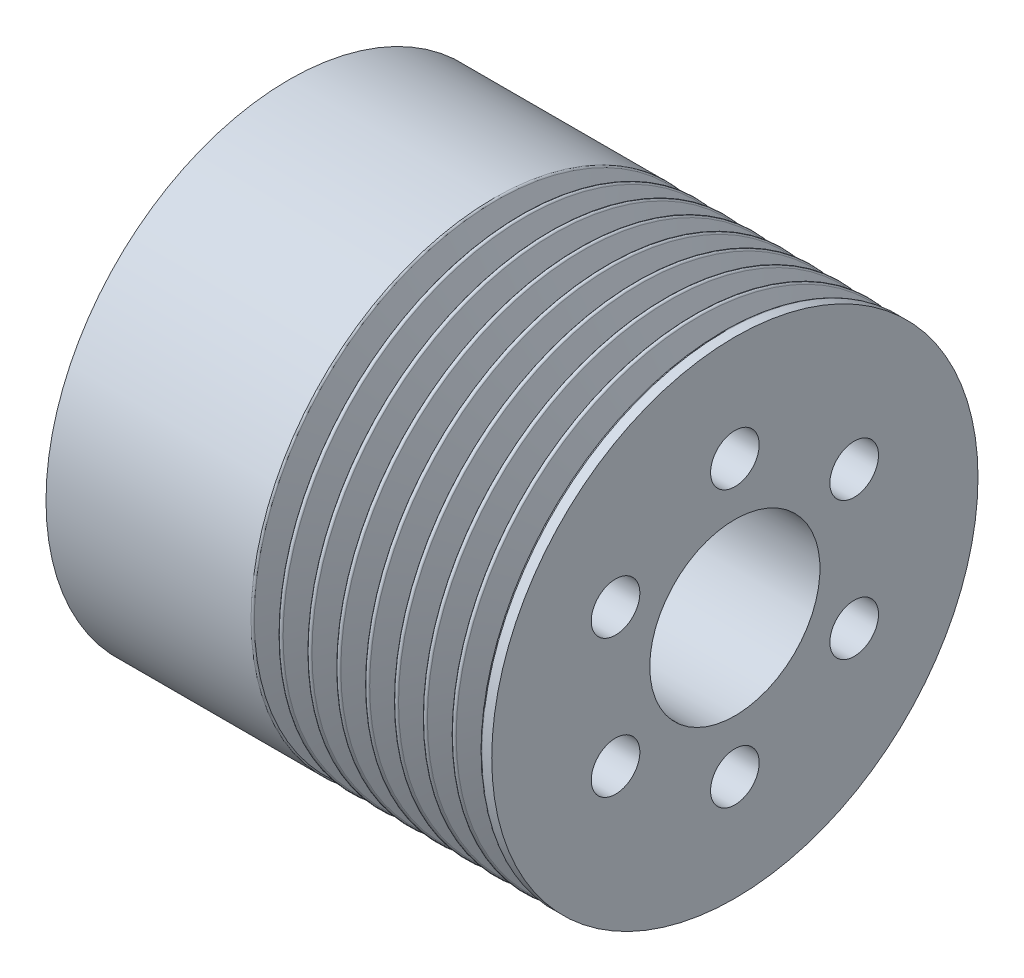
SolidWorks part; units mm, degrees
material "2018 Alloy"
ref_plane "Front Plane" through (0, 0, 0) normal (0, 0, 1) x (1, 0, 0)
ref_plane "Top Plane" through (0, 0, 0) normal (0, 1, 0) x (1, 0, 0)
ref_plane "Right Plane" through (0, 0, 0) normal (1, 0, 0) x (0, 0, -1)
sketch "Sketch1" plane through (0, 0, 0) normal (0, 0, 1) x (1, 0, 0)
  line L0 (49, 10.5) -> (49, 0) construction
  line L1 (49, 10.5) -> (49, 30)
  line L2 (49, 30) -> (-6, 30)
  line L3 (-6, 30) -> (-6, 21.5)
  line L4 (49, 10.5) -> (31.5, 10.5)
  line L5 (0, 0) -> (49, 0) construction
  line L6 (-6, 21.5) -> (31.5, 21.5)
  line L8 (0, 8.3175) -> (0, 0) construction
  line L9 (31.5, 10.5) -> (31.5, 21.5)
  dimension "D1" = 55
  dimension "D2" = 60
  dimension "D3" = 31.5
  dimension "D4" = 43
  dimension "D5" = 49
  dimension "D8" = 21
revolve "Revolve1" add sketch "Sketch1" angle 360 about L5
sketch "Sketch2" plane through (0, 0, 0) normal (0, 0, 1) x (1, 0, 0)
  line L0 (47.5451, 29.8355) -> (46.2819, 26.365)
  line L1 (45.7181, 26.365) -> (44.4549, 29.8355)
  line L2 (47.5451, 29.8355) -> (47.6049, 30) construction
  line L3 (49, 30) -> (-6, 30) construction
  line L4 (44.4549, 29.8355) -> (44.3951, 30) construction
  line L5 (49, -30) -> (49, 30) construction
  line L6 (47.78, 30) -> (44.22, 30)
  line L7 (0, 0) -> (49, 0) construction
  arc A0 (47.5451, 29.8355) -> (47.78, 30) centre (47.78, 29.75) cw
  arc A1 (44.4549, 29.8355) -> (44.22, 30) centre (44.22, 29.75) ccw
  arc A2 (46.2819, 26.365) -> (45.7181, 26.365) centre (46, 26.4676) cw
  dimension "D2" = 0.25
  dimension "D3" = 0.3
  dimension "D1" = 40
  dimension "D4" = 3.56
  dimension "D5" = 3
revolve "Cut-Revolve1" cut sketch "Sketch2" angle 360 about L7
pattern_linear "LPattern1" count 8 spacing 3.56 along (-1, 0, 0) of "Cut-Revolve1"
sketch "Sketch3" plane through (49, 0, 0) normal (1, 0, 0) x (0, 0, -1)
  circle A0 centre (0, 0) radius 17 construction
  circle A1 centre (0, 17) radius 3
  circle A2 centre (14.7224, 8.5) radius 3
  circle A3 centre (14.7224, -8.5) radius 3
  circle A4 centre (0, -17) radius 3
  circle A5 centre (-14.7224, -8.5) radius 3
  circle A6 centre (-14.7224, 8.5) radius 3
  dimension "D1" = 34
  dimension "D2" = 6
  dimension "D3" = 6
extrude "Cut-Extrude1" cut sketch "Sketch3" against normal up to surface (17.5 mm away) up to face at (31.5, 0, 10.5)
